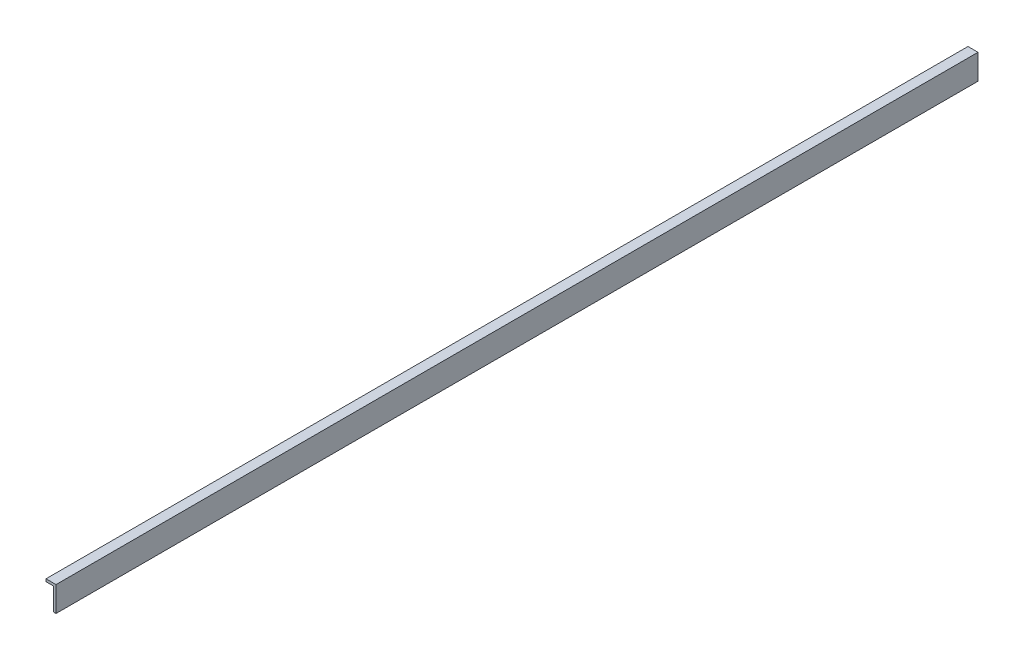
SolidWorks part; units mm, degrees
ref_plane "Front Plane" through (0, 0, 0) normal (0, 0, 1) x (1, 0, 0)
ref_plane "Top Plane" through (0, 0, 0) normal (0, 1, 0) x (1, 0, 0)
ref_plane "Right Plane" through (0, 0, 0) normal (1, 0, 0) x (0, 0, -1)
other "Configuration Table"
sketch "Sketch1" plane through (0, 0, 0) normal (0, 0, 1) x (1, 0, 0)
  line L0 (205.5, 404.5) -> (207.5, 404.5)
  line L1 (207.5, 404.5) -> (207.5, 424.5)
  line L2 (207.5, 424.5) -> (199.5, 424.5)
  line L3 (199.5, 424.5) -> (199.5, 422.5)
  line L4 (199.5, 422.5) -> (205.5, 422.5)
  line L5 (205.5, 422.5) -> (205.5, 404.5)
extrude "STORE_kaset_L_raf_1_sag_1" add sketch "Sketch1" against normal blind 735.5 from offset 20 separate body
